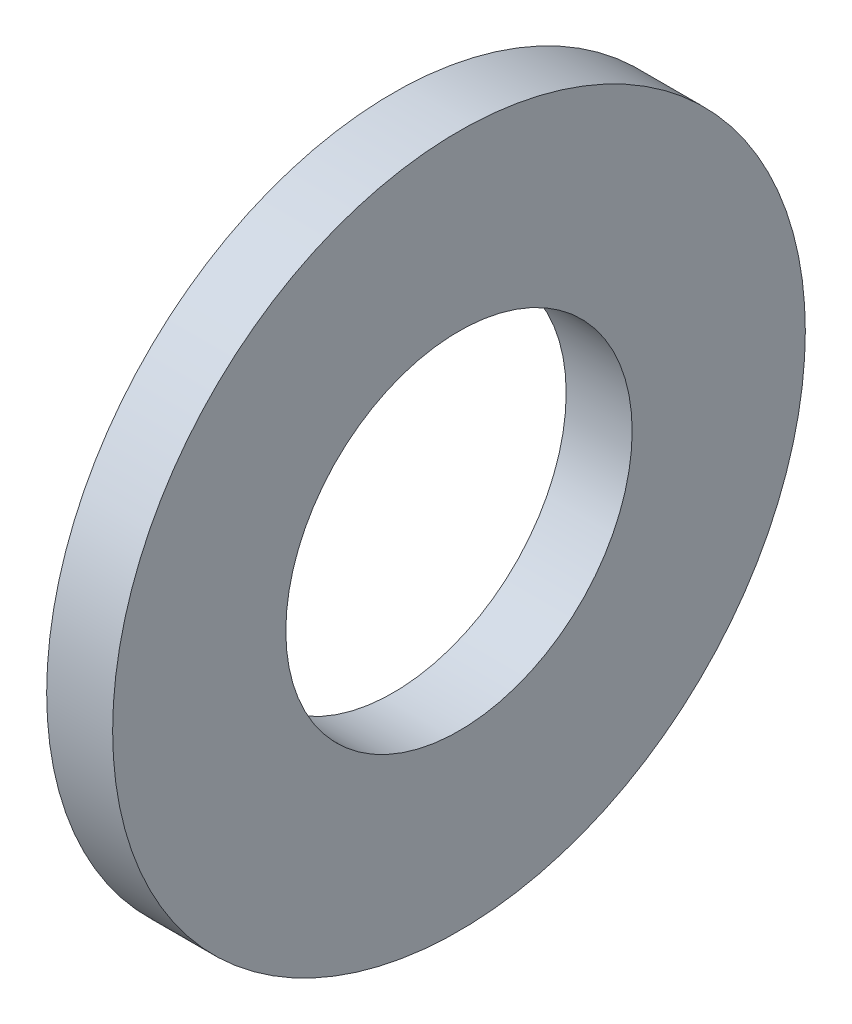
SolidWorks part; units mm, degrees
ref_plane "Plane1" through (0, 0, 0) normal (0, 0, 1) x (1, 0, 0)
ref_plane "Plane2" through (0, 0, 0) normal (0, 1, 0) x (1, 0, 0)
ref_plane "Plane3" through (0, 0, 0) normal (1, 0, 0) x (0, 0, -1)
sketch "Sketch1" plane through (0, 0, 0) normal (0, 0, 1) x (1, 0, 0)
  line L0 (-34.925, 0) -> (9.525, 0) construction
  line L1 (0, 5.25) -> (0, 10.5)
  line L2 (0, 10.5) -> (-2, 10.5)
  line L3 (-2, 10.5) -> (-2, 5.25)
  line L4 (-2, 5.25) -> (0, 5.25)
  dimension "Thickness" = 2
  dimension "Inside_dia" = 10.5
  dimension "Outside_dia" = 21
revolve "Base-Revolve" add sketch "Sketch1" angle 360 about L0
